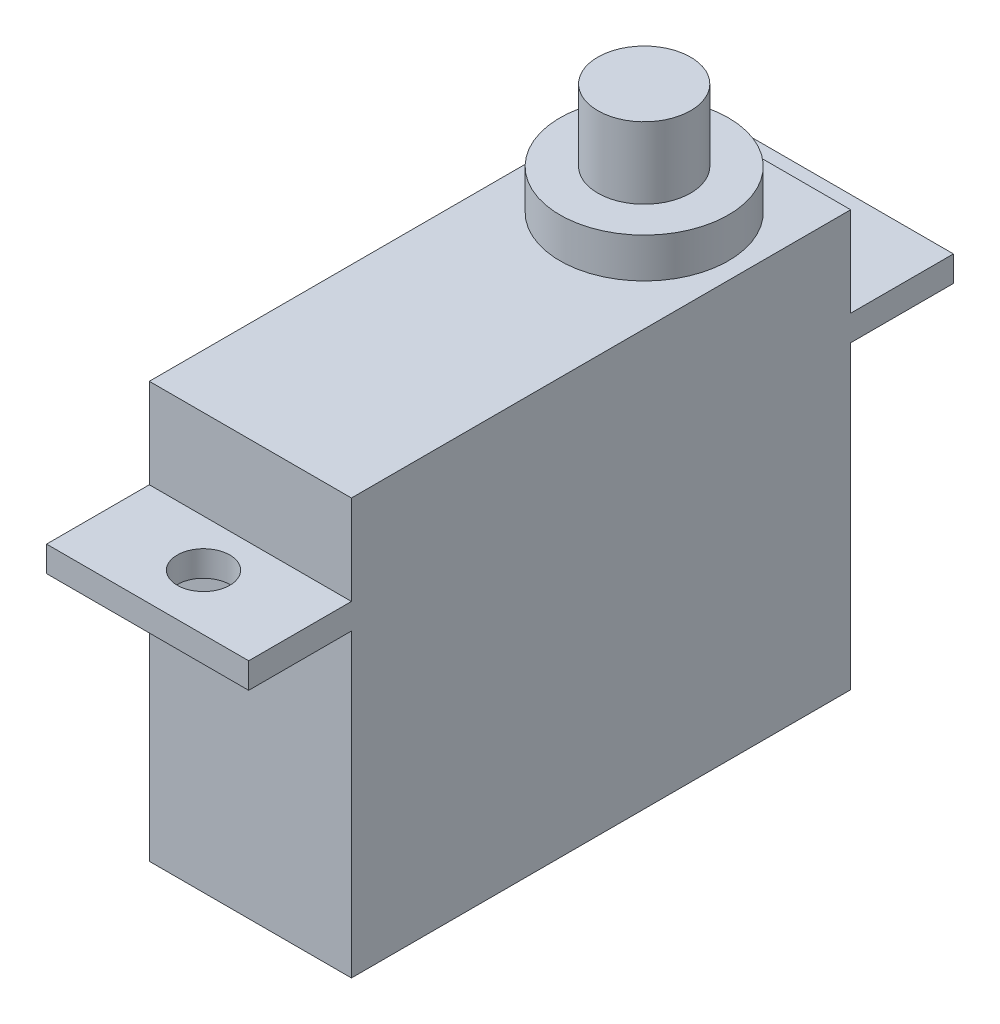
SolidWorks part; units mm, degrees
ref_plane "Front Plane" through (0, 0, 0) normal (0, 0, 1) x (1, 0, 0)
ref_plane "Top Plane" through (0, 0, 0) normal (0, 1, 0) x (1, 0, 0)
ref_plane "Right Plane" through (0, 0, 0) normal (1, 0, 0) x (0, 0, -1)
sketch "Sketch1" plane through (0, 0, 0) normal (0, 1, 0) x (1, 0, 0)
  line L1 (0, 0) -> (7.62, 0)
  line L2 (0, 0) -> (0, 18.8214)
  line L3 (0, 18.8214) -> (7.62, 18.8214)
  line L4 (7.62, 0) -> (7.62, 18.8214)
  dimension "D1" = 7.62
  dimension "D2" = 18.8214
extrude "Boss-Extrude1" add sketch "Sketch1" along normal blind 15.6718
ref_plane "Plane1" through (0, 11.3284, 0) normal (0, -1, 0) x (-1, 0, 0)
sketch "Sketch2" plane through (0, 11.3284, 0) normal (0, -1, 0) x (-1, 0, 0)
  line L0 (0, 9.4107) -> (-7.62, 9.4107) construction
  line L1 (0, 18.8214) -> (-7.62, 18.8214)
  line L2 (0, 18.8214) -> (0, 22.6949)
  line L3 (0, 22.6949) -> (-5.08, 22.6949)
  line L4 (-7.62, 18.8214) -> (-7.62, 22.6949)
  line L5 (0, 18.8214) -> (0, 0) construction
  line L6 (-7.62, 0) -> (-7.62, 18.8214) construction
  line L7 (-3.81, 31.5955) -> (-3.81, 18.8214) construction
  line L8 (-3.81, -12.7741) -> (-3.81, 0) construction
  line L9 (-7.62, 0) -> (-7.62, -3.8735)
  line L10 (0, 0) -> (0, -3.8735)
  line L11 (0, 0) -> (-7.62, 0)
  line L12 (0, -3.8735) -> (-5.08, -3.8735)
  line L17 (-2.54, 22.6949) -> (-7.62, 22.6949)
  line L18 (-2.54, -3.8735) -> (-7.62, -3.8735)
  circle A0 centre (-3.81, 20.5867) radius 0.9906
  circle A1 centre (-3.81, -1.7653) radius 0.9906
  dimension "D3" = 1.9812
  dimension "D1" = 26.5684
  dimension "D2" = 22.352
extrude "Boss-Extrude2" add sketch "Sketch2" against normal blind 0.9652
sketch "Sketch3" plane through (0, 15.6718, 0) normal (0, 1, 0) x (1, 0, 0)
  line L0 (3.81, 20.5867) -> (3.81, 14.8463) construction
  circle A0 centre (3.81, 14.8463) radius 3.175
  dimension "D2" = 6.35
  dimension "D1" = 5.7404
extrude "Boss-Extrude3" add sketch "Sketch3" along normal blind 1.4986
sketch "Sketch4" plane through (0, 17.1704, 0) normal (0, 1, 0) x (1, 0, 0)
  circle A0 centre (3.81, 14.8463) radius 1.75
  dimension "D1" = 3.5
extrude "Boss-Extrude4" add sketch "Sketch4" along normal blind 2.6924
